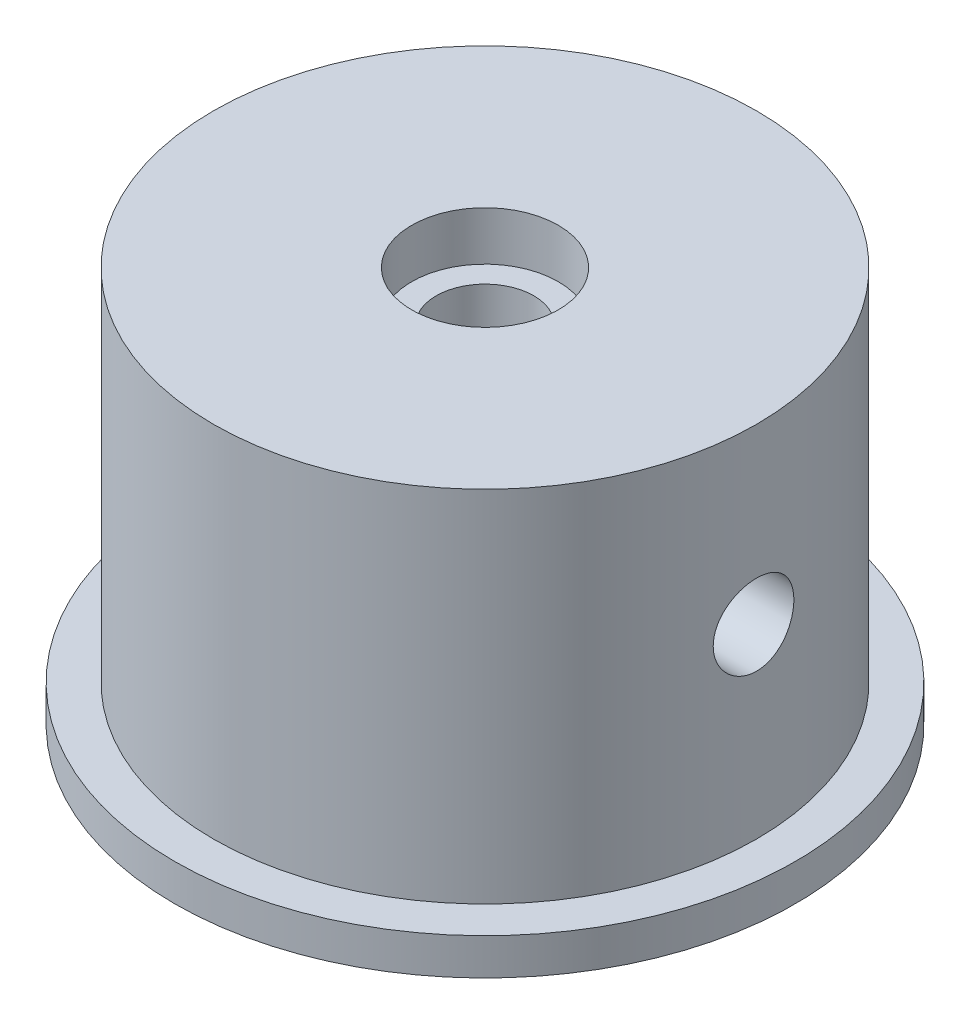
SolidWorks part; units mm, degrees
material "ABS"
ref_plane "Front Plane" through (0, 0, 0) normal (0, 0, 1) x (1, 0, 0)
ref_plane "Top Plane" through (0, 0, 0) normal (0, 1, 0) x (1, 0, 0)
ref_plane "Right Plane" through (0, 0, 0) normal (1, 0, 0) x (0, 0, -1)
sketch "Sketch1" plane through (0, 0, 0) normal (1, 0, 0) x (0, 0, -1)
  line L0 (-2, 0) -> (-3, 0)
  line L1 (-3, 0) -> (-3, -2)
  line L2 (-3, -2) -> (-12.7, -2)
  line L3 (-12.7, -2) -> (-12.7, -0.5)
  line L4 (-12.7, -0.5) -> (-11.1125, -0.5)
  line L5 (-11.1125, -0.5) -> (-11.1125, 14.2)
  line L6 (-11.1125, 14.2) -> (-3, 14.2)
  line L7 (-3, 14.2) -> (-3, 12.2)
  line L8 (-3, 12.2) -> (-2, 12.2)
  line L9 (-2, 12.2) -> (-2, 0)
  line L10 (0, -1000) -> (0, 49000) construction
  dimension "D1" = 12.7
  dimension "D2" = 11.1125
  dimension "D3" = 3
  dimension "D4" = 12.2
  dimension "D5" = 2
  dimension "D6" = 2
  dimension "D7" = 1.5
revolve "Revolve1" add sketch "Sketch1" angle 360 about L10
sketch "Sketch2" plane through (0, 0, 0) normal (1, 0, 0) x (0, 0, -1)
  line L0 (0, 0) -> (0, 14.2) construction
  line L1 (3, 14.2) -> (-3, 14.2) construction
  circle A0 centre (0, 7.1) radius 1.65
  point P8 (0, 7.1)
  dimension "D1" = 3.3
extrude "Cut-Extrude1" cut sketch "Sketch2" against normal up to next from offset 5.5 offset against normal yes
mirror "Mirror1" about plane through (0, 0, 0) normal (1, 0, 0) of "Cut-Extrude1"
